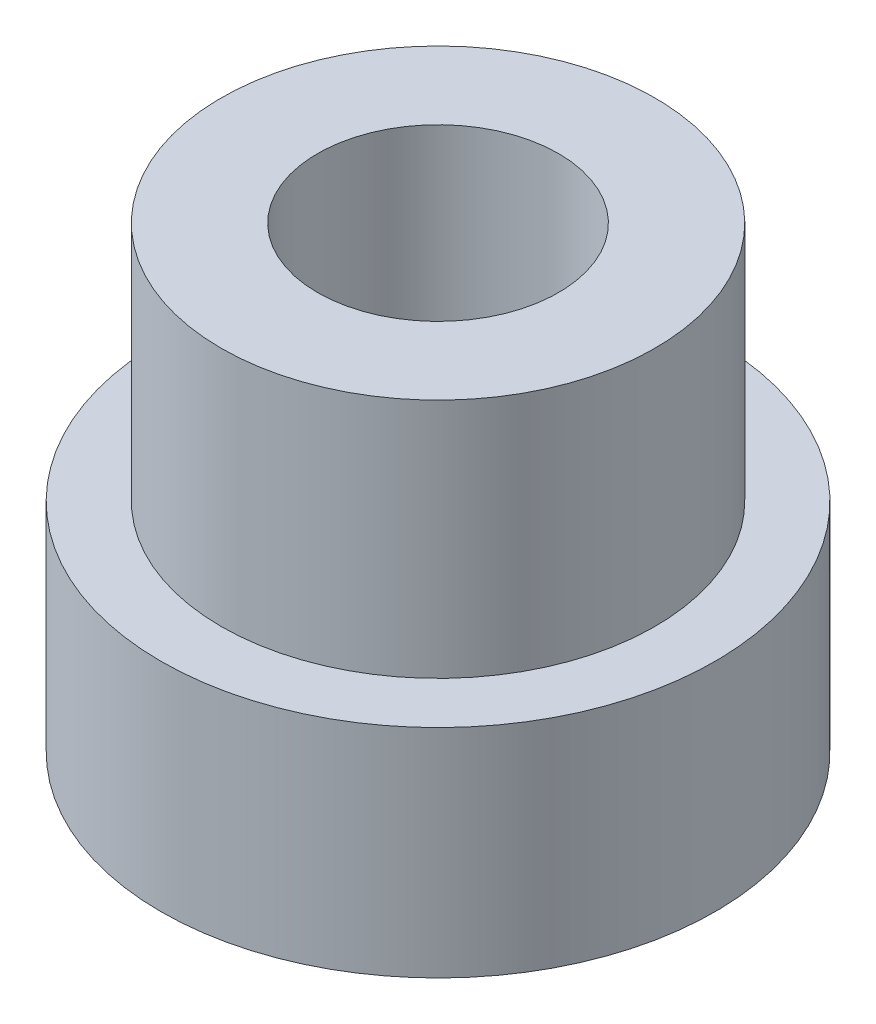
SolidWorks part; units mm, degrees
ref_plane "Front Plane" through (0, 0, 0) normal (0, 0, 1) x (1, 0, 0)
ref_plane "Top Plane" through (0, 0, 0) normal (0, 1, 0) x (1, 0, 0)
ref_plane "Right Plane" through (0, 0, 0) normal (1, 0, 0) x (0, 0, -1)
sketch "Sketch1" plane through (0, 0, 0) normal (0, 1, 0) x (1, 0, 0)
  circle A0 centre (0, 0) radius 23
  dimension "D1" = 46
extrude "Boss-Extrude1" add sketch "Sketch1" along normal blind 18
sketch "Sketch2" plane through (0, 18, 0) normal (0, 1, 0) x (1, 0, 0)
  circle A0 centre (0, 0) radius 18
  dimension "D1" = 36
extrude "Boss-Extrude2" add sketch "Sketch2" along normal blind 20
sketch "Sketch3" plane through (0, 0, 0) normal (0, -1, 0) x (-1, 0, 0)
  circle A0 centre (0, 0) radius 8
  dimension "D1" = 16
extrude "Cut-Extrude1" cut sketch "Sketch3" against normal blind 8
sketch "Sketch4" plane through (0, 38, 0) normal (0, 1, 0) x (1, 0, 0)
  circle A0 centre (0, 0) radius 10
  dimension "D1" = 20
extrude "Cut-Extrude2" cut sketch "Sketch4" against normal blind 20
hole_wizard "Ø10.0mm Dowel Slot1" positions "Sketch5" profile "Sketch6" size "Ø10.0" standard "ISO" slot yes end condition up to next
sketch "Sketch5" plane through (0, 18, 0) normal (0, 1, 0) x (1, 0, 0)
  point P0 (0, 0)
sketch "Sketch6" plane through (0, 18, 0) normal (1, 0, 0) x (0, 0, 1)
  line L0 (0, 0) -> (0, 10)
  line L1 (0, 10) -> (5, 10)
  line L2 (5, 10) -> (5, 0)
  line L5 (5, 0) -> (0, 0)
  line L11 (0, -6.35) -> (0, 107.95) construction
  dimension "Thru Hole Dia." = 10
  dimension "Thru Hole Depth" = 10
